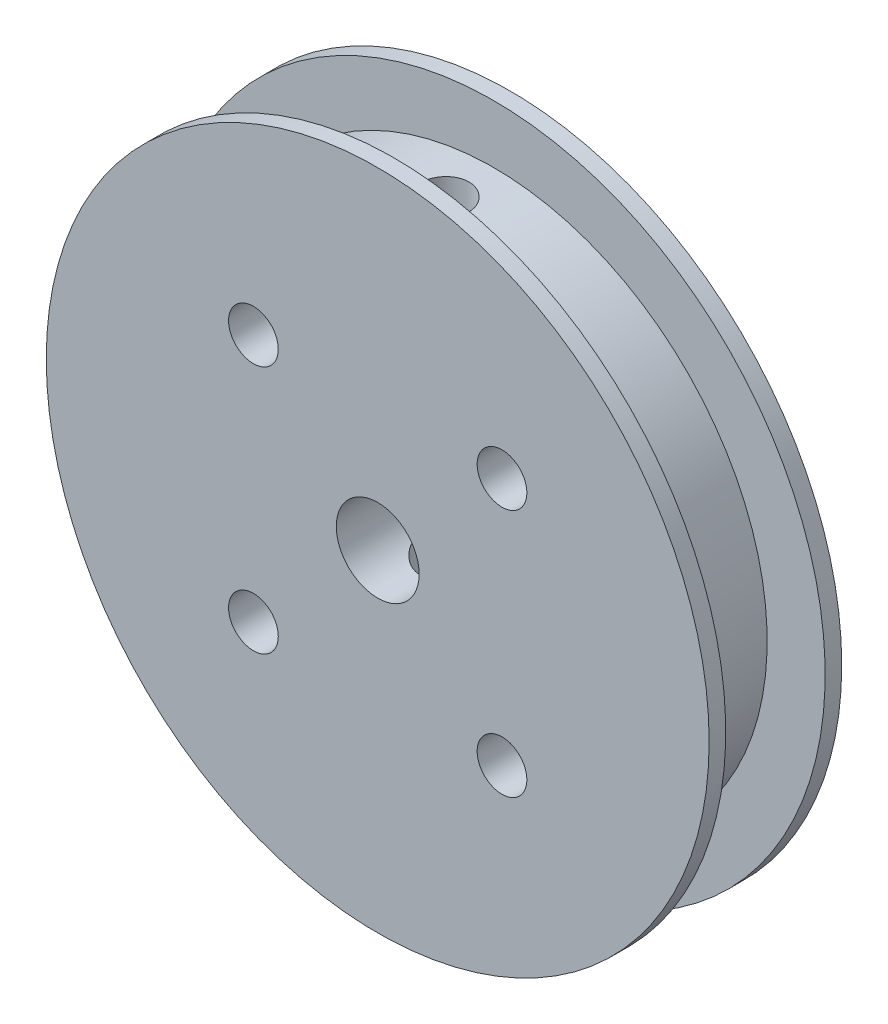
SolidWorks part; units mm, degrees
material "Acrylic (Medium-high impact)"
ref_plane "Front Plane" through (0, 0, 0) normal (0, 0, 1) x (1, 0, 0)
ref_plane "Top Plane" through (0, 0, 0) normal (0, 1, 0) x (1, 0, 0)
ref_plane "Right Plane" through (0, 0, 0) normal (1, 0, 0) x (0, 0, -1)
sketch "Sketch1" plane through (0, 0, 0) normal (0, 0, 1) x (1, 0, 0)
  circle A0 centre (0, 0) radius 20
  dimension "D1" = 40
extrude "Pulley Boss-Extrude1" add sketch "Sketch1" along normal blind 8
sketch "Sketch2" plane through (0, 0, 0) normal (0, 1, 0) x (1, 0, 0)
  line L0 (20, -8) -> (20, 0) construction
  line L1 (20, -1) -> (16.5, -1)
  line L2 (20, -1) -> (20, -7)
  line L3 (20, -7) -> (16.5, -7)
  line L4 (16.5, -1) -> (16.5, 0) construction
  line L5 (0, 14.6216) -> (0, -23.6188) construction
  line L6 (16.5, -1) -> (16.5, -7)
  line L7 (20, 0) -> (-20, 0) construction
  line L10 (16.5, -7) -> (16.5, -8) construction
  line L11 (-20, -8) -> (20, -8) construction
  dimension "D1" = 6
  dimension "D2" = 3.5
  dimension "D3" = 16.5
revolve "Belt Cut-Revolve3" cut sketch "Sketch2" angle 360 about L5
sketch "Sketch3" plane through (0, 0, 0) normal (0, 0, 1) x (1, 0, 0)
  circle A0 centre (0, 0) radius 2.5
  dimension "D1" = 5
extrude "Shaft Cut-Extrude1" cut sketch "Sketch3" along normal up to surface (8 mm away) up to face at (20, 0, 8)
sketch "Sketch4" plane through (0, 0, 0) normal (0, 1, 0) x (1, 0, 0)
  line L0 (0, 0) -> (0, -4) construction
  line L1 (0, -4) -> (0, -8) construction
  line L2 (-20, -8) -> (20, -8) construction
  circle A0 centre (0, -4) radius 1.5
  dimension "D1" = 3
extrude "Sprint Hole Cut-Extrude2" cut sketch "Sketch4" against normal up to surface and the other way up to surface up to face at (-16.5, 0, 7) other way up to face at (-16.5, 0, 7)
sketch "Sketch5" plane through (0, 0, 8) normal (0, 0, 1) x (1, 0, 0)
  line L0 (-7.5, 7.5) -> (0, 0) construction
  line L1 (-7.5, 7.5) -> (7.5, 7.5) construction
  line L2 (-7.5, 7.5) -> (-7.5, -7.5) construction
  line L3 (-7.5, -7.5) -> (7.5, -7.5) construction
  line L4 (7.5, 7.5) -> (7.5, -7.5) construction
  line L5 (7.5, 7.5) -> (0, 0) construction
  line L6 (7.5, -7.5) -> (0, 0) construction
  line L7 (0, 0) -> (-7.5, -7.5) construction
  circle A0 centre (0, 0) radius 20 construction
  circle A1 centre (0, 0) radius 8 construction
  circle A2 centre (7.5, 7.5) radius 1.5
  circle A3 centre (-7.5, 7.5) radius 1.5
  circle A4 centre (-7.5, -7.5) radius 1.5
  circle A5 centre (7.5, -7.5) radius 1.5
  dimension "D1" = 40
  dimension "D3" = 16
  dimension "D4" = 3
  dimension "D2" = 15
extrude "Arm Distans Mounting Holes Cut-Extrude1" cut sketch "Sketch5" against normal up to surface (8 mm away) up to face at (20, 0, 0)
